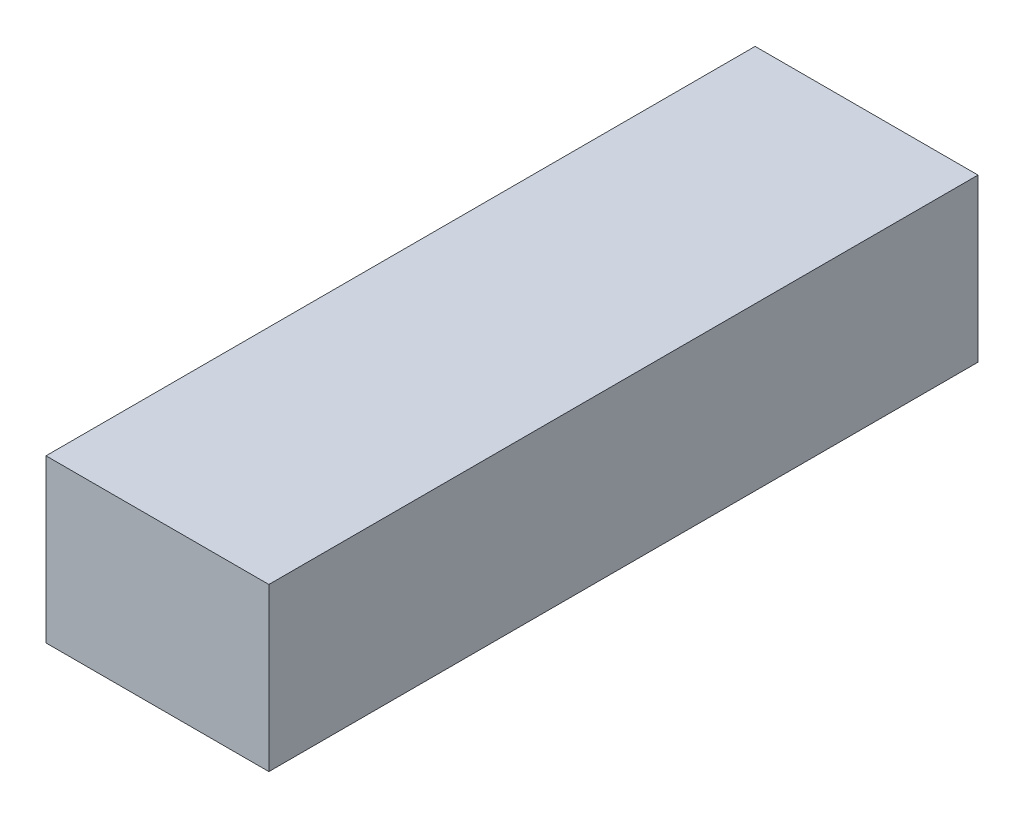
SolidWorks part; units mm, degrees
ref_plane "Front Plane" through (0, 0, 0) normal (0, 0, 1) x (1, 0, 0)
ref_plane "Top Plane" through (0, 0, 0) normal (0, 1, 0) x (1, 0, 0)
ref_plane "Right Plane" through (0, 0, 0) normal (1, 0, 0) x (0, 0, -1)
sketch "Sketch1" plane through (0, 0, 0) normal (0, 1, 0) x (1, 0, 0)
  line L0 (-573.6248, 0) -> (28107.6174, 0) construction
  line L1 (0, -573.6248) -> (0, 28107.6174) construction
  line L3 (-16.5, 52.5) -> (16.5, 52.5)
  line L4 (-16.5, 52.5) -> (-16.5, -52.5)
  line L5 (-16.5, -52.5) -> (16.5, -52.5)
  line L6 (16.5, 52.5) -> (16.5, -52.5)
  line L7 (-16.5, 52.5) -> (16.5, -52.5) construction
  line L8 (-16.5, -52.5) -> (16.5, 52.5) construction
  point P4 (0, 0)
  dimension "D1" = 33
  dimension "D2" = 105
extrude "Boss-Extrude1" add sketch "Sketch1" along normal blind 24
equation "\"Frame_Size\" = 220"
equation "\"Frame_Thickness\" = 6"
equation "\"Arm_Width\" = 30"
equation "\"Motor_Mount_Hole_Diameter\" = 8"
equation "\"Motor_Shaft_Diameter\" = 3"
equation "\"Screw_Nut_Diameter\" = 6.5"
equation "\"Screw_Diameter\" = 3"
equation "\"Screw_Shaft_Length\" = 8"
equation "\"Screw_Hole_Separation_C2C\" = 20"
equation "\"Solder_Board_Small_Screw_Hole_Separation\" = 37"
equation "\"Solder_Board_Small_Screw_Hole_Diameter\" = 3.3"
equation "\"Solder_Board_Small_Length\" = 45.72"
equation "\"Solder_Board_Small_Width\" = 33.02"
equation "\"Solder_Board_Small_Thickness\" = 1.6"
equation "\"ESC_Length\" = 35"
equation "\"ESC_Width\" = 17"
equation "\"ESC_Thickness\" = 5"
equation "\"Battery_Length\" = 105"
equation "\"Battery_Width\" = 33"
equation "\"Battery_Thickness\" = 24"
equation "\"D1@Sketch1\"=\"Battery_Width\""
equation "\"D1@Boss-Extrude1\"=\"Battery_Thickness\""
